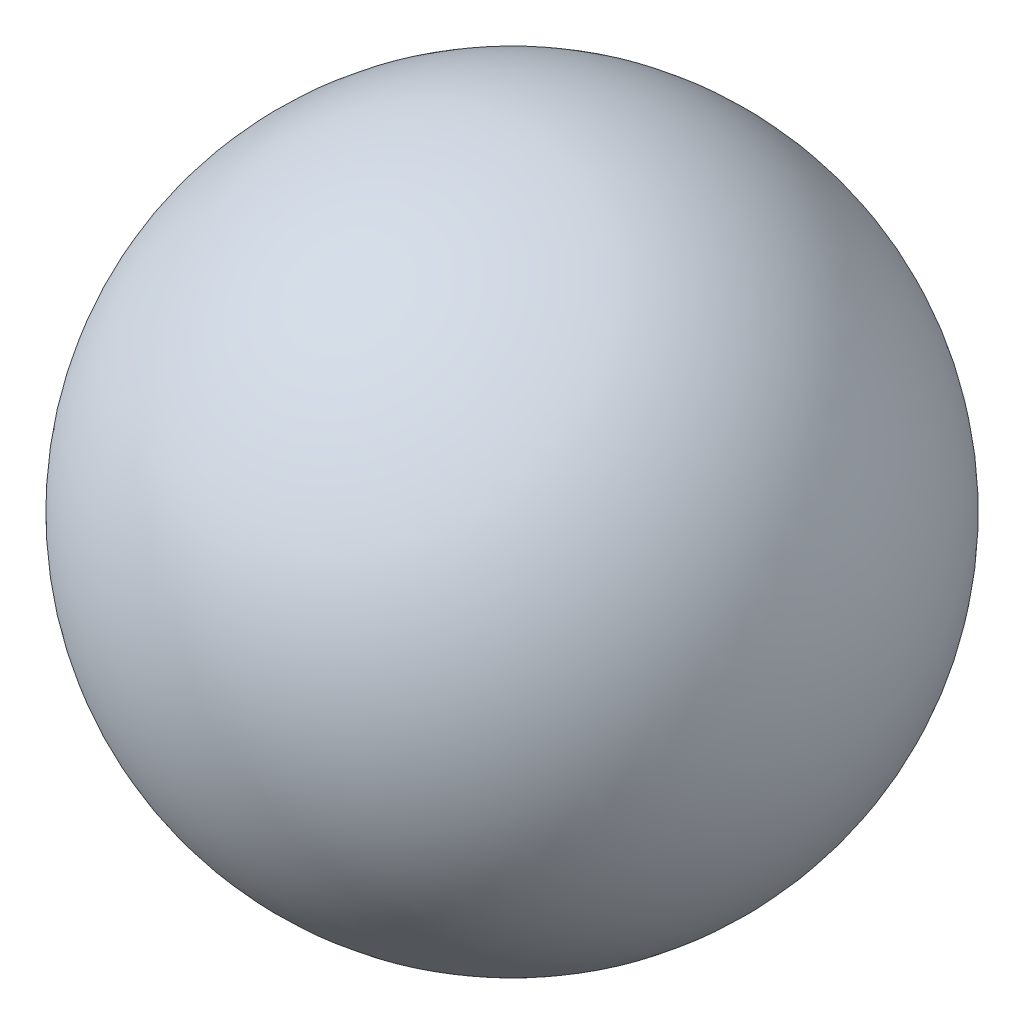
SolidWorks part; units mm, degrees
material "Plain Carbon Steel"
ref_plane "Front Plane" through (0, 0, 0) normal (0, 0, 1) x (1, 0, 0)
ref_plane "Top Plane" through (0, 0, 0) normal (0, 1, 0) x (1, 0, 0)
ref_plane "Right Plane" through (0, 0, 0) normal (1, 0, 0) x (0, 0, -1)
sketch "Profile" plane through (0, 0, 0) normal (0, 0, 1) x (1, 0, 0)
  line L0 (0, 2.6938) -> (0, -2.9778) construction
  line L1 (0, 1.25) -> (0, -1.25)
  arc A0 (0, -1.25) -> (0, 1.25) centre (0, 0) ccw
  dimension "D1" = 2.5
revolve "Ball" add sketch "Profile" angle 360 about L0
